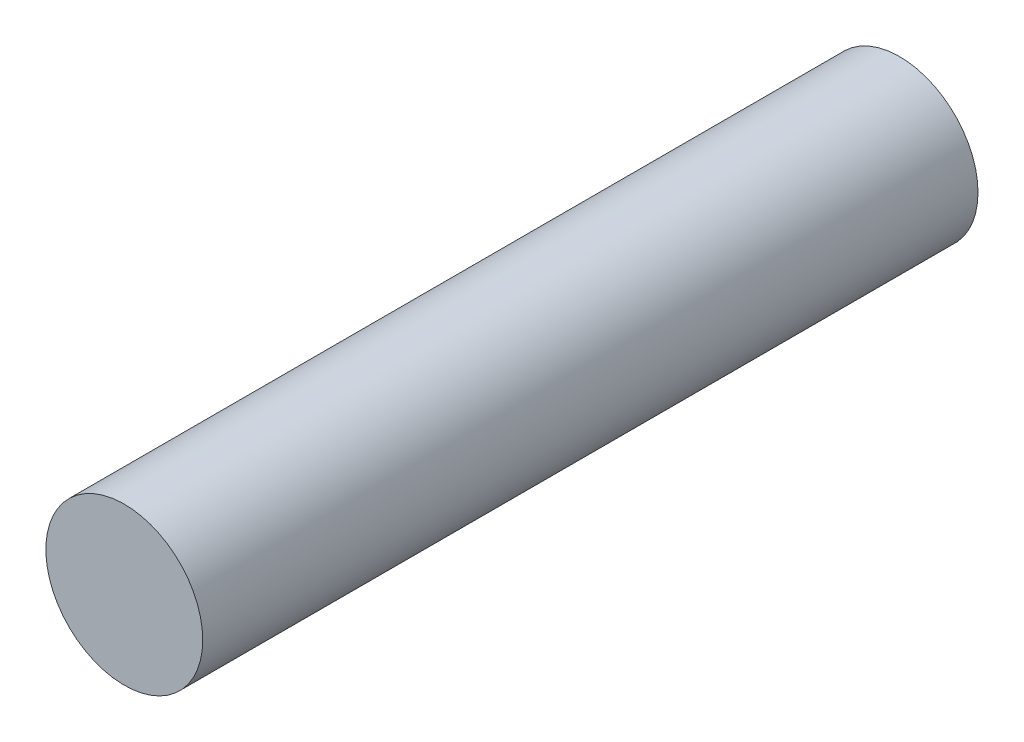
SolidWorks part; units mm, degrees
ref_plane "Front Plane" through (0, 0, 0) normal (0, 0, 1) x (1, 0, 0)
ref_plane "Top Plane" through (0, 0, 0) normal (0, 1, 0) x (1, 0, 0)
ref_plane "Right Plane" through (0, 0, 0) normal (1, 0, 0) x (0, 0, -1)
sketch "Sketch1" plane through (0, 0, 0) normal (0, 0, 1) x (1, 0, 0)
  circle A0 centre (0, 0) radius 0.85
  dimension "D1" = 1.7
extrude "Boss-Extrude1" add sketch "Sketch1" along normal blind 8.4
